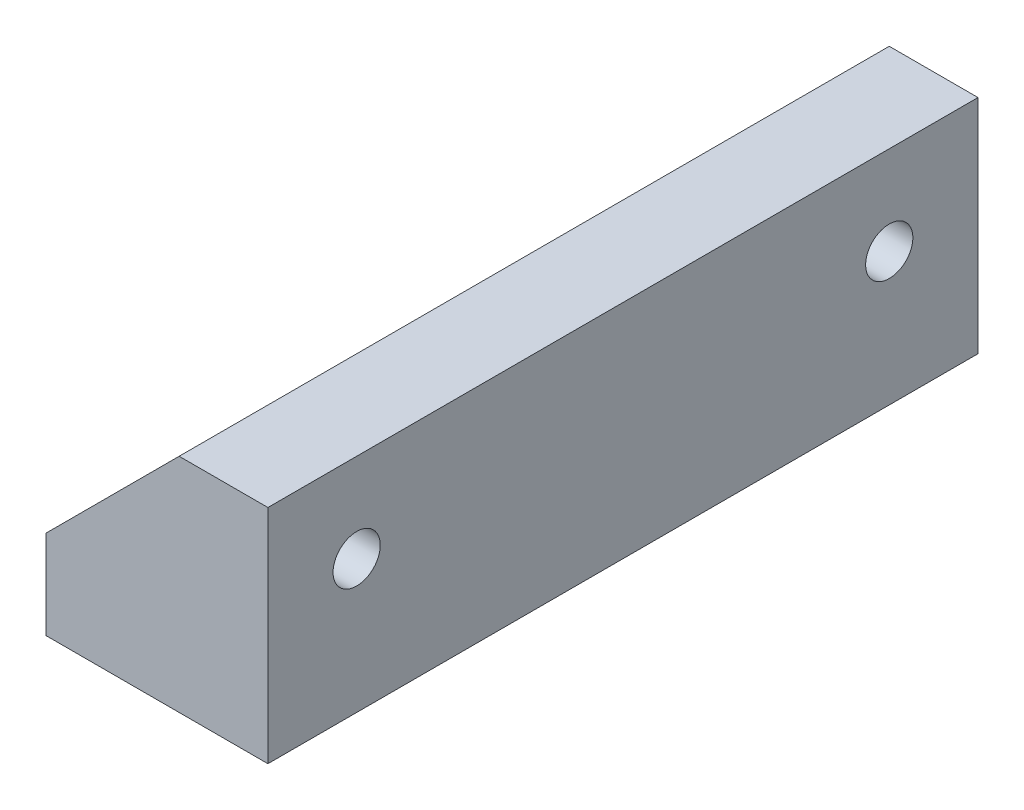
SolidWorks part; units mm, degrees
ref_plane "Front" through (0, 0, 0) normal (0, 0, 1) x (1, 0, 0)
ref_plane "Top" through (0, 0, 0) normal (0, 1, 0) x (1, 0, 0)
ref_plane "Right" through (0, 0, 0) normal (1, 0, 0) x (0, 0, -1)
sketch "Sketch1" plane through (0, 0, 0) normal (0, 1, 0) x (1, 0, 0)
  line L1 (-15.875, -50.8) -> (15.875, -50.8)
  line L2 (-15.875, -50.8) -> (-15.875, 50.8)
  line L3 (-15.875, 50.8) -> (15.875, 50.8)
  line L4 (15.875, -50.8) -> (15.875, 50.8)
  line L5 (-15.875, -50.8) -> (15.875, 50.8) construction
  line L6 (-15.875, 50.8) -> (15.875, -50.8) construction
  point P0 (0, 0)
  dimension "D1" = 101.6
  dimension "D2" = 31.75
extrude "Boss-Extrude1" add sketch "Sketch1" along normal mid plane 31.75 contours L3 L4 L1 L2
sketch "Sketch2" plane through (0, 0, 50.8) normal (0, 0, 1) x (1, 0, 0)
  line L0 (-15.875, -3.175) -> (-15.875, 15.875)
  line L1 (-15.875, 15.875) -> (-15.875, -15.875) construction
  line L2 (-15.875, 15.875) -> (3.175, 15.875)
  line L3 (-15.875, 15.875) -> (15.875, 15.875) construction
  line L4 (3.175, 15.875) -> (-15.875, -3.175)
  line L5 (15.875, 15.875) -> (15.875, -15.875) construction
  dimension "D1" = 45
  dimension "D2" = 12.7
extrude "Cut-Extrude1" cut sketch "Sketch2" against normal up to next
sketch "Sketch3" plane through (-6.35, 6.35, 0) normal (-0.7071, 0.7071, 0) x (0, 0, 1)
  line L0 (-25.4, 0) -> (25.4, 0) construction
  line L1 (50.8, -13.4704) -> (50.8, 13.4704) construction
  line L2 (0, -50) -> (0, 50) construction
  point P0 (-25.4, 0)
  point P1 (25.4, 0)
  point P6 (50.8, 0)
  point P7 (0, 0)
  dimension "D1" = 50.8
hole_wizard "1/4-20 Tapped Hole1" positions "Sketch4" profile "Sketch6" tap size "1/4-20" standard "ANSI Inch"
sketch "Sketch4" plane through (-6.35, 6.35, 0) normal (-0.7071, 0.7071, 0) x (0, 0, 1)
  point P0 (-25.4, 0)
  point P3 (25.4, 0)
sketch "Sketch6" plane through (-6.35, 6.35, -25.4) normal (0, 0, 1) x (-0.7071, -0.7071, 0)
  line L0 (0, 0) -> (0, 14.2338)
  line L1 (0, 14.2338) -> (2.5527, 12.7)
  line L2 (2.5527, 12.7) -> (2.5527, 0)
  line L5 (2.5527, 0) -> (0, 0)
  line L10 (0, 14.2338) -> (-2.5527, 12.7) construction
  line L11 (0, -6.35) -> (0, 107.95) construction
  dimension "Tap Drill Dia." = 5.1054
  dimension "Tap Drill Depth" = 12.7
  dimension "Drill Angle" = 118
cosmetic thread "Hole Thread1" parameters "D1"=12.7, "D2"=6.35
cosmetic thread "Hole Thread2" parameters "D1"=12.7, "D2"=6.35
ref_plane "Plane1" through (-15.875, 0, 0) normal (-1, 0, 0) x (0, 0, 1)
sketch "Sketch7" plane through (-15.875, 0, 0) normal (1, 0, 0) x (0, 0, -1)
  line L0 (-38.1, 3.175) -> (38.1, 3.175) construction
  line L1 (0, 50) -> (0, -50) construction
  line L2 (-50.8, 15.875) -> (-50.8, -15.875) construction
  line L3 (-50.8, 15.875) -> (50.8, 15.875) construction
  point P0 (-38.1, 3.175)
  point P1 (38.1, 3.175)
  point P2 (0, 3.175)
  dimension "D1" = 12.7
  dimension "D2" = 12.7
hole_wizard "CBORE for 1/4 Socket Head Cap Screw1" positions "Sketch14" profile "Sketch15" counterbore size "1/4" standard "ANSI Inch" end condition through all
sketch "Sketch14" plane through (-15.875, 0, 0) normal (-1, 0, 0) x (0, 0, 1)
  point P0 (-38.1, 3.175)
  point P3 (38.1, 3.175)
sketch "Sketch15" plane through (-15.875, 3.175, -38.1) normal (0, 1, 0) x (0, 0, 1)
  line L0 (0, 0) -> (0, 31.75)
  line L1 (0, 31.75) -> (3.3782, 31.75)
  line L3 (3.3782, 31.75) -> (3.3782, 20.32)
  line L4 (3.3782, 20.32) -> (5.5562, 20.32)
  line L5 (5.5562, 20.32) -> (5.5562, 0)
  line L7 (5.5562, 0) -> (0, 0)
  line L11 (0, -6.35) -> (0, 107.95) construction
  dimension "Thru Hole Dia." = 6.7564
  dimension "Thru Hole Depth" = 31.75
  dimension "C'Bore Dia." = 11.1125
  dimension "C'Bore Depth" = 20.32
